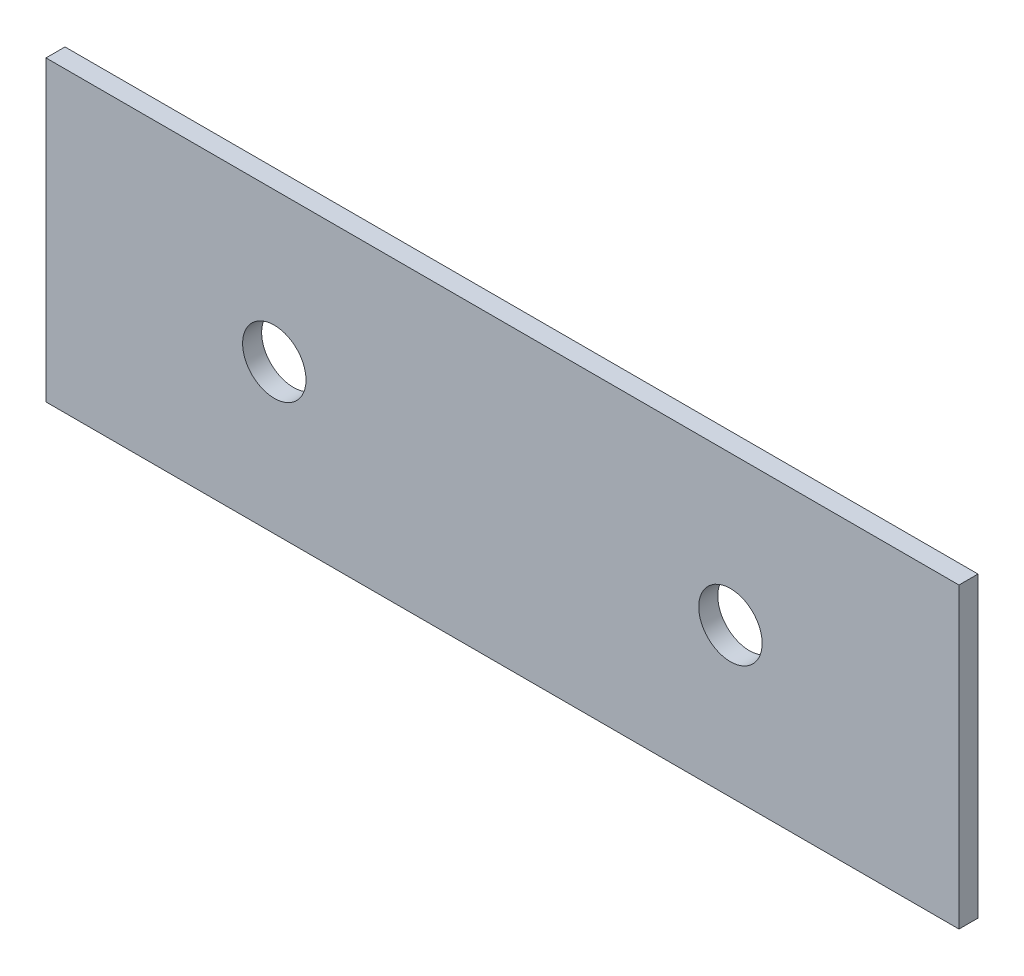
SolidWorks part; units mm, degrees
ref_plane "Front Plane" through (0, 0, 0) normal (0, 0, 1) x (1, 0, 0)
ref_plane "Top Plane" through (0, 0, 0) normal (0, 1, 0) x (1, 0, 0)
ref_plane "Right Plane" through (0, 0, 0) normal (1, 0, 0) x (0, 0, -1)
sketch "Sketch1" plane through (0, 0, 0) normal (0, 0, 1) x (1, 0, 0)
  line L0 (15.6443, 243.1814) -> (159.6443, 243.1814)
  line L1 (159.6443, 243.1814) -> (159.6443, 196.1814)
  line L2 (159.6443, 196.1814) -> (15.6443, 196.1814)
  line L3 (15.6443, 196.1814) -> (15.6443, 243.1814)
  dimension "D1" = 47
  dimension "D2" = 144
extrude "Boss-Extrude1" add sketch "Sketch1" along normal blind 3 contours L3 L0 L1 L2
ref_plane "Plane3" through (159.6443, 243.1814, 3) normal (0, -1, 0) x (-1, 0, 0)
sketch "Sketch5" plane through (0, 0, 3) normal (0, 0, 1) x (1, 0, 0)
  line L0 (15.6443, 219.6814) -> (159.6443, 219.6814)
  line L1 (15.6443, 196.1814) -> (15.6443, 243.1814) construction
  line L2 (159.6443, 243.1814) -> (159.6443, 196.1814) construction
  line L3 (87.6443, 243.1814) -> (87.6443, 196.1814)
  line L4 (15.6443, 243.1814) -> (159.6443, 243.1814) construction
  line L5 (159.6443, 196.1814) -> (15.6443, 196.1814) construction
  line L6 (15.6443, 219.6814) -> (51.6526, 219.6814) construction
  line L7 (159.6443, 219.6814) -> (123.5979, 219.6814) construction
  circle A0 centre (51.6526, 219.6814) radius 5
  circle A1 centre (123.5979, 219.6814) radius 5
extrude "Cut-Extrude2" cut sketch "Sketch5" against normal blind 10 contours L0 A0 | L0 A0 | L0 A1 | L0 A1
